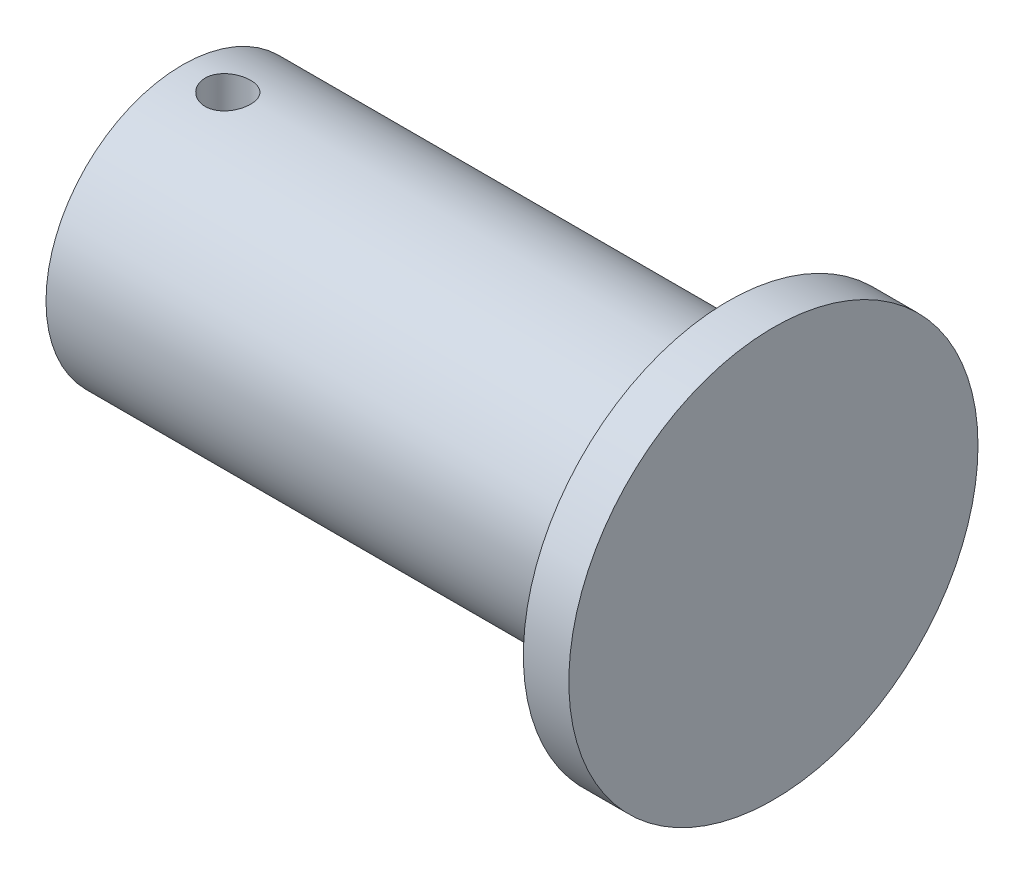
SolidWorks part; units mm, degrees
ref_plane "Front Plane" through (0, 0, 0) normal (0, 0, 1) x (1, 0, 0)
ref_plane "Top Plane" through (0, 0, 0) normal (0, 1, 0) x (1, 0, 0)
ref_plane "Right Plane" through (0, 0, 0) normal (1, 0, 0) x (0, 0, -1)
sketch "Sketch1" plane through (0, 0, 0) normal (1, 0, 0) x (0, 0, -1)
  circle A0 centre (0, 0) radius 15
  dimension "D1" = 30
extrude "Boss-Extrude1" add sketch "Sketch1" along normal mid plane 60
sketch "Sketch2" plane through (30, 0, 0) normal (1, 0, 0) x (0, 0, -1)
  circle A0 centre (0, 0) radius 22.5
  dimension "D1" = 45
extrude "Boss-Extrude2" add sketch "Sketch2" along normal blind 5
sketch "Sketch3" plane through (0, 0, 0) normal (0, 1, 0) x (1, 0, 0)
  line L0 (-30, 15) -> (-30, -15) construction
  circle A0 centre (-25, 0) radius 2.5
  dimension "D1" = 5
  dimension "D2" = 5
extrude "Cut-Extrude1" cut sketch "Sketch3" against normal through all both and the other way through all
